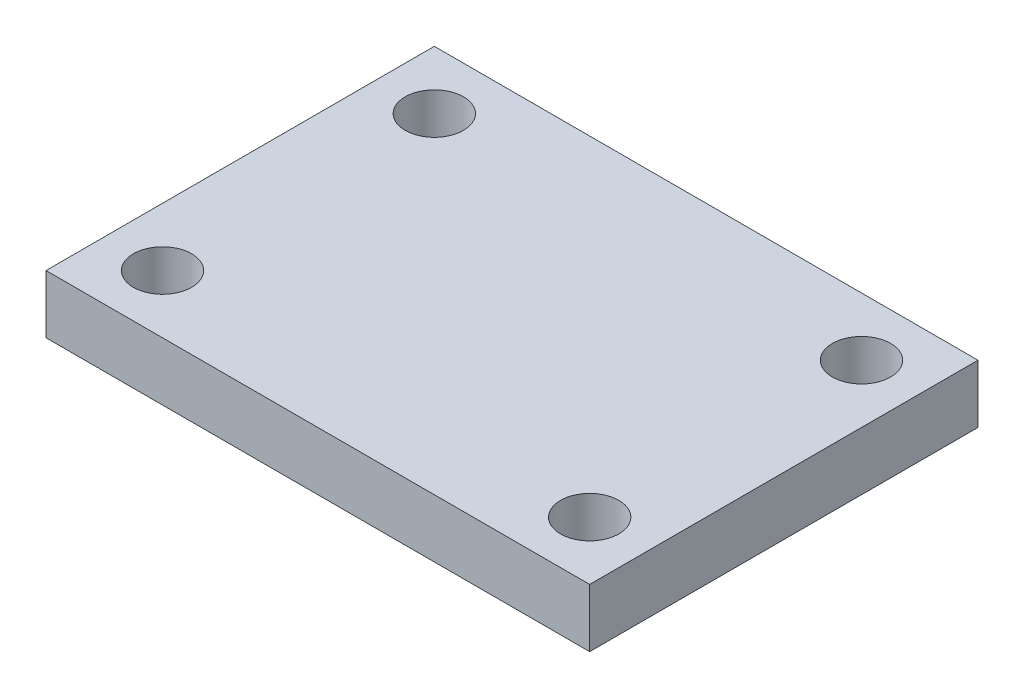
SolidWorks part; units mm, degrees
ref_plane "Front Plane" through (0, 0, 0) normal (0, 0, 1) x (1, 0, 0)
ref_plane "Top Plane" through (0, 0, 0) normal (0, 1, 0) x (1, 0, 0)
ref_plane "Right Plane" through (0, 0, 0) normal (1, 0, 0) x (0, 0, -1)
sketch "Sketch1" plane through (0, 0, 0) normal (0, 1, 0) x (1, 0, 0)
  line L0 (0, 16.4974) -> (0, -16.278) construction
  line L1 (14, -10) -> (-14, -10)
  line L2 (14, -10) -> (14, 10)
  line L3 (14, 10) -> (-14, 10)
  line L4 (-14, -10) -> (-14, 10)
  line L5 (14, -10) -> (-14, 10) construction
  line L6 (14, 10) -> (-14, -10) construction
  circle A0 centre (-11, 7) radius 1.5
  circle A1 centre (-11, -7) radius 1.5
  circle A2 centre (11, -7) radius 1.5
  circle A3 centre (11, 7) radius 1.5
  point P0 (0, 0)
  dimension "D7" = 3
  dimension "D1" = 14
  dimension "D2" = 28
  dimension "D3" = 20
  dimension "D4" = 3
  dimension "D5" = 3
  dimension "D6" = 22
extrude "Boss-Extrude1" add sketch "Sketch1" along normal blind 3
